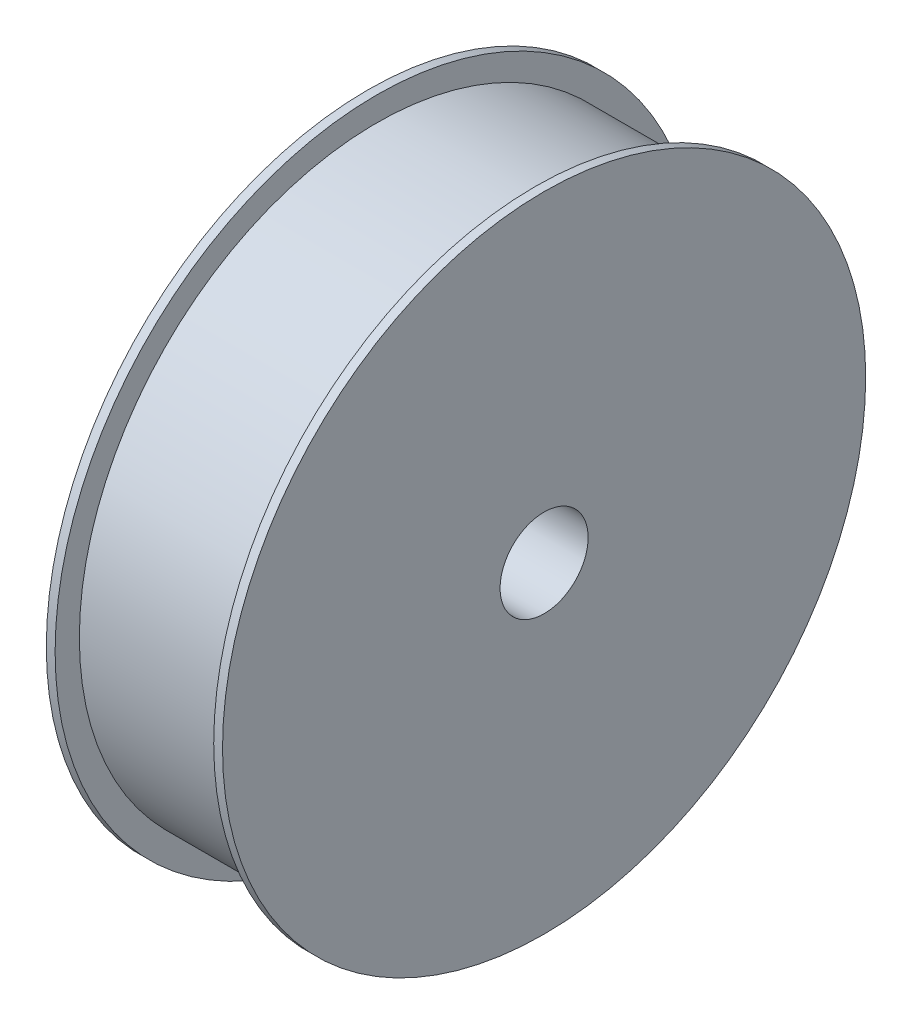
SolidWorks part; units mm, degrees
ref_plane "Front Plane" through (0, 0, 0) normal (0, 0, 1) x (1, 0, 0)
ref_plane "Top Plane" through (0, 0, 0) normal (0, 1, 0) x (1, 0, 0)
ref_plane "Right Plane" through (0, 0, 0) normal (1, 0, 0) x (0, 0, -1)
sketch "Sketch1" plane through (0, 0, 0) normal (0, 0, 1) x (1, 0, 0)
  line L0 (-58.1666, 0) -> (60.2282, 0) construction
  line L4 (64.9308, 36.5) -> (63.9308, 36.5)
  line L5 (63.9308, 36.5) -> (63.9308, 33.75)
  line L6 (63.9308, 33.75) -> (45.9308, 33.75)
  line L7 (45.9308, 33.75) -> (45.9308, 36.5)
  line L8 (45.9308, 36.5) -> (44.9308, 36.5)
  line L13 (44.9308, 29.0817) -> (44.9308, 25)
  line L14 (44.9308, 5) -> (64.9308, 5)
  line L16 (44.9308, 29.0817) -> (44.9308, 36.5)
  line L17 (64.9308, 36.5) -> (64.9308, 5)
  line L19 (44.9308, 5) -> (37.9308, 5)
  line L21 (44.9308, 25) -> (37.9308, 25)
  line L22 (37.9308, 5) -> (37.9308, 25)
  dimension "D1" = 1
  dimension "D2" = 33.75
  dimension "D3" = 5
  dimension "D4" = 25
  dimension "D5" = 1
  dimension "D6" = 36.5
  dimension "D7" = 7
  dimension "D8" = 18
revolve "Revolve1" add sketch "Sketch1" angle 360 about L0
